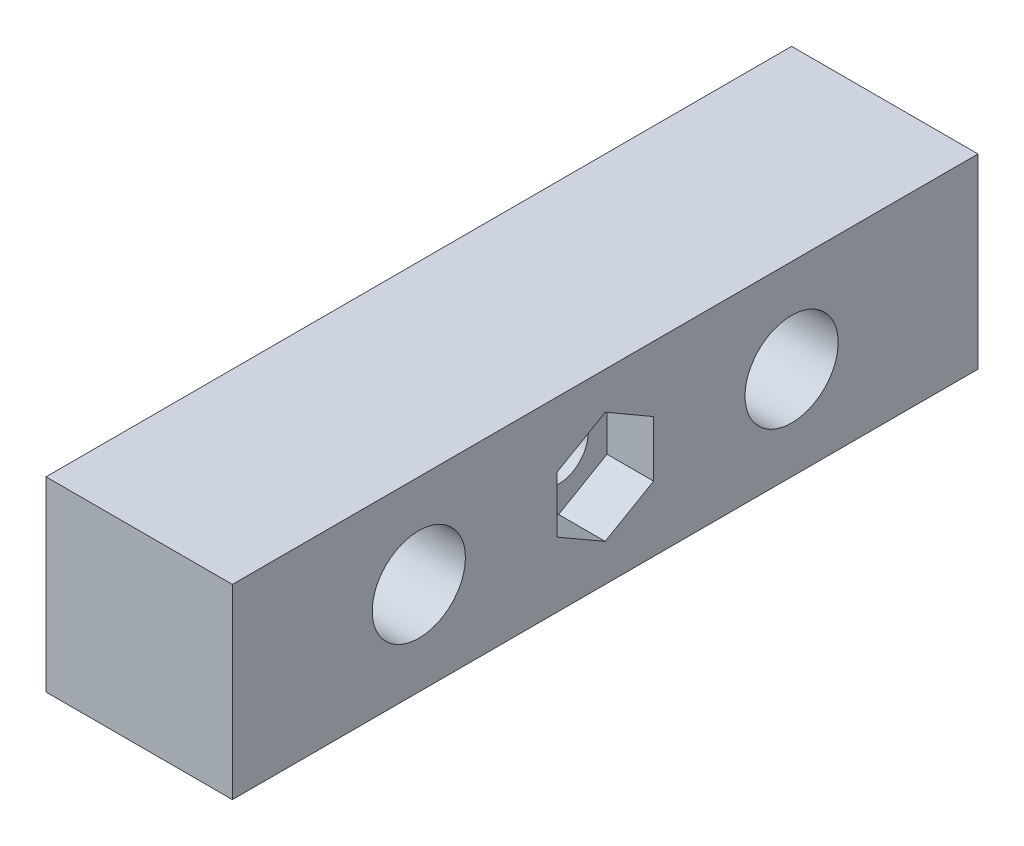
SolidWorks part; units mm, degrees
ref_plane "Front Plane" through (0, 0, 0) normal (0, 0, 1) x (1, 0, 0)
ref_plane "Top Plane" through (0, 0, 0) normal (0, 1, 0) x (1, 0, 0)
ref_plane "Right Plane" through (0, 0, 0) normal (1, 0, 0) x (0, 0, -1)
sketch "Sketch1" plane through (0, 0, 0) normal (0, 1, 0) x (1, 0, 0)
  line L1 (-10, -40) -> (10, -40)
  line L2 (-10, -40) -> (-10, 40)
  line L3 (-10, 40) -> (10, 40)
  line L4 (10, -40) -> (10, 40)
  line L5 (-10, -40) -> (10, 40) construction
  line L6 (-10, 40) -> (10, -40) construction
  point P0 (0, 0)
  dimension "D1" = 80
  dimension "D2" = 20
extrude "Boss-Extrude1" add sketch "Sketch1" along normal blind 20
sketch "Sketch2" plane through (10, 0, 0) normal (1, 0, 0) x (0, 0, -1)
  line L0 (-40, 10) -> (40, 10) construction
  line L1 (-40, 20) -> (-40, 0) construction
  line L2 (40, 20) -> (40, 0) construction
  line L3 (0, 20) -> (0, 0) construction
  line L4 (-40, 20) -> (40, 20) construction
  line L5 (-40, 0) -> (40, 0) construction
  circle A0 centre (-20, 10) radius 5
  circle A1 centre (20, 10) radius 5
  dimension "D1" = 10
  dimension "D2" = 40
extrude "Cut-Extrude1" cut sketch "Sketch2" against normal through all
sketch "Sketch5" plane through (10, 0, 0) normal (1, 0, 0) x (0, 0, -1)
  line L0 (0, 20) -> (0, 0) construction
  line L1 (-40, 20) -> (40, 20) construction
  line L2 (-40, 0) -> (40, 0) construction
  circle A0 centre (0, 10) radius 3.175
  dimension "D1" = 6.35
extrude "Cut-Extrude4" cut sketch "Sketch5" against normal through all
sketch "Sketch3" plane through (10, 0, 0) normal (1, 0, 0) x (0, 0, -1)
  line L0 (0, 20) -> (0, 0) construction
  line L1 (-40, 20) -> (40, 20) construction
  line L2 (-40, 0) -> (40, 0) construction
  line L4 (0, 16) -> (-5.1962, 13)
  line L5 (-5.1962, 13) -> (-5.1962, 7)
  line L6 (-5.1962, 7) -> (0, 4)
  line L7 (0, 4) -> (5.1962, 7)
  line L8 (5.1962, 7) -> (5.1962, 13)
  line L9 (5.1962, 13) -> (0, 16)
  circle A0 centre (0, 10) radius 5.1962 construction
  dimension "D1" = 6
extrude "Cut-Extrude3" cut sketch "Sketch3" against normal blind 5
ref_plane "Plane1" through (0, 0, 0) normal (1, 0, 0) x (0, 0, -1)
mirror "Mirror1" about plane through (0, 0, 0) normal (1, 0, 0) of "Cut-Extrude3"
sketch "Sketch6" plane through (0, 0, 0) normal (0, -1, 0) x (1, 0, 0)
  line L0 (10, 0) -> (-10, 0) construction
  line L1 (10, 40) -> (10, -40) construction
  line L2 (-10, -40) -> (-10, 40) construction
